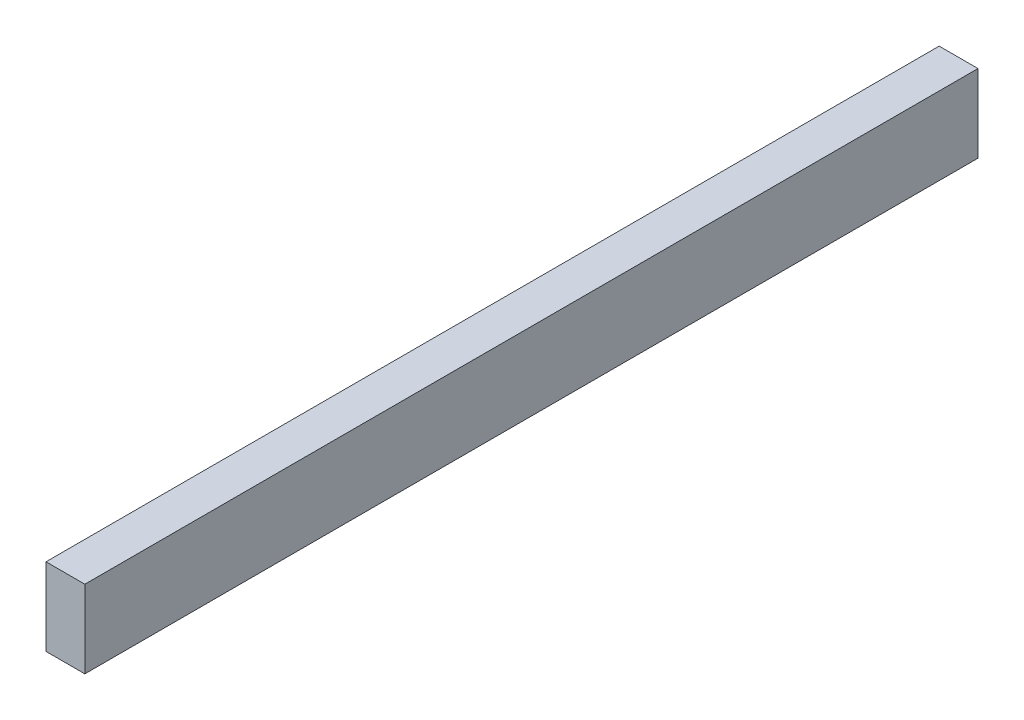
SolidWorks part; units mm, degrees
ref_plane "Front Plane" through (0, 0, 0) normal (0, 0, 1) x (1, 0, 0)
ref_plane "Top Plane" through (0, 0, 0) normal (0, 1, 0) x (1, 0, 0)
ref_plane "Right Plane" through (0, 0, 0) normal (1, 0, 0) x (0, 0, -1)
sketch "Sketch1" plane through (0, 0, 0) normal (0, 0, 1) x (1, 0, 0)
  line L1 (-12.7, 25.4) -> (12.7, 25.4)
  line L2 (-12.7, 25.4) -> (-12.7, -25.4)
  line L3 (-12.7, -25.4) -> (12.7, -25.4)
  line L4 (12.7, 25.4) -> (12.7, -25.4)
  line L5 (-12.7, 25.4) -> (12.7, -25.4) construction
  line L6 (-12.7, -25.4) -> (12.7, 25.4) construction
  point P0 (0, 0)
extrude "Boss-Extrude1" add sketch "Sketch1" along normal blind 584.2
